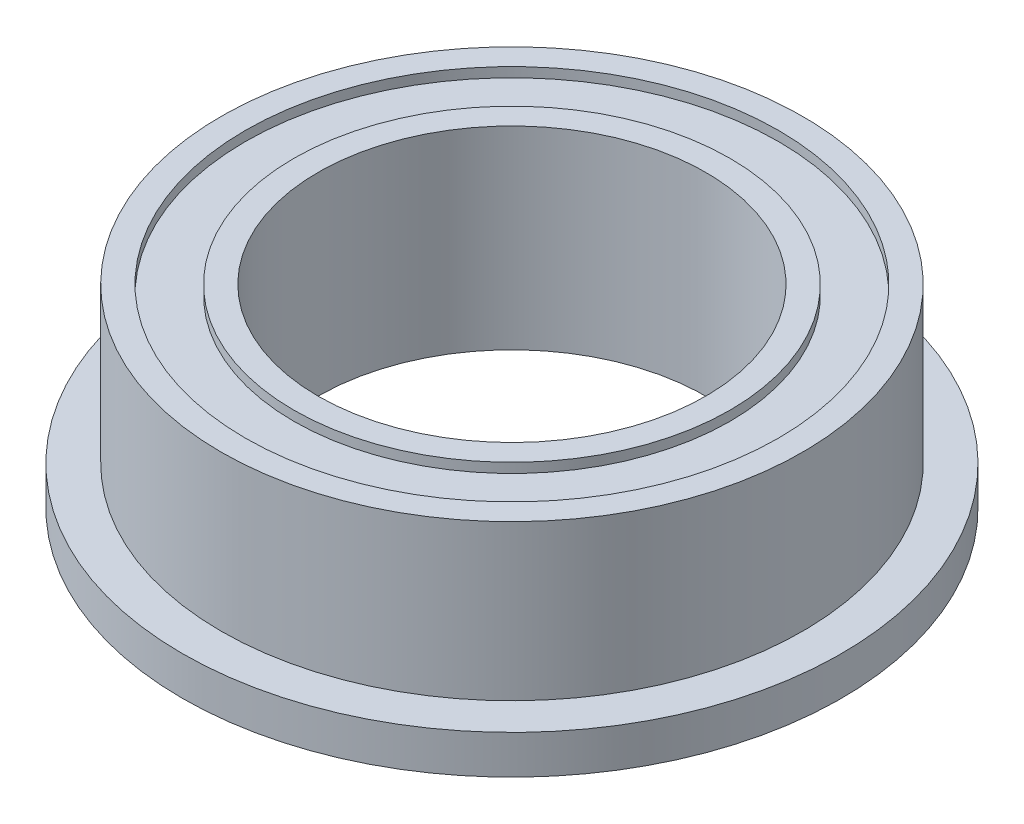
SolidWorks part; units mm, degrees
ref_plane "前视基准面" through (0, 0, 0) normal (0, 0, 1) x (1, 0, 0)
ref_plane "上视基准面" through (0, 0, 0) normal (0, 1, 0) x (1, 0, 0)
ref_plane "右视基准面" through (0, 0, 0) normal (1, 0, 0) x (0, 0, -1)
other "Configuration Table"
sketch "草图1" plane through (0, 0, 0) normal (0, 1, 0) x (1, 0, 0)
  circle A0 centre (0, 0) radius 6
  circle A1 centre (0, 0) radius 4
  dimension "D1" = 12
  dimension "D2" = 8
extrude "凸台-拉伸1" add sketch "草图1" along normal blind 4
sketch "草图2" plane through (0, 0, 0) normal (0, 1, 0) x (1, 0, 0)
  circle A0 centre (0, 0) radius 6.8
  circle A1 centre (0, 0) radius 6
  dimension "D1" = 12
  dimension "D2" = 13.6
extrude "凸台-拉伸2" add sketch "草图2" along normal blind 0.8
sketch "草图3" plane through (0, 4, 0) normal (0, 1, 0) x (1, 0, 0)
  circle A0 centre (0, 0) radius 4.5
  circle A1 centre (0, 0) radius 5.5
  circle A2 centre (0, 0) radius 6 construction
  circle A3 centre (0, 0) radius 4 construction
  dimension "D1" = 0.5
  dimension "D2" = 0.5
extrude "切除-拉伸1" cut sketch "草图3" against normal blind 0.2
ref_plane "基准面1" through (0, 2, 0) normal (0, 1, 0) x (1, 0, 0)
mirror "镜向1" about plane through (0, 2, 0) normal (0, 1, 0) of "切除-拉伸1"
